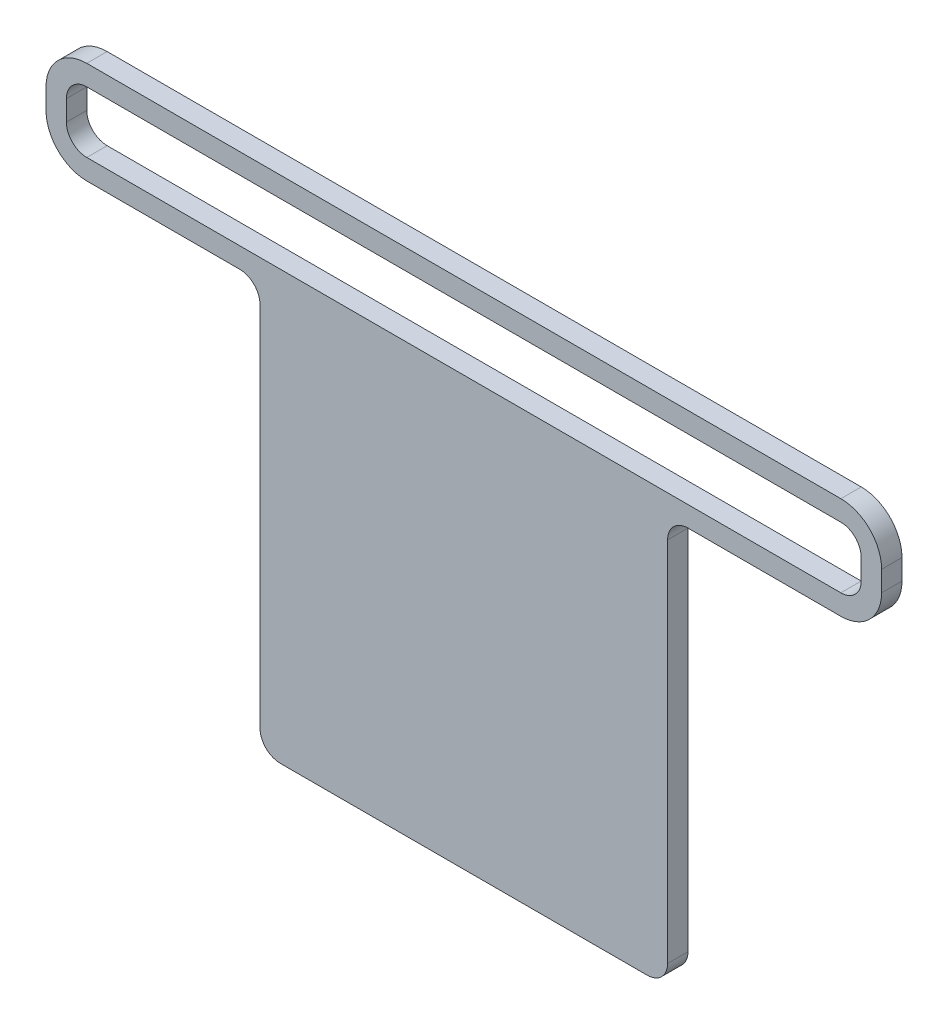
SolidWorks part; units mm, degrees
ref_plane "Front Plane" through (0, 0, 0) normal (0, 0, 1) x (1, 0, 0)
ref_plane "Top Plane" through (0, 0, 0) normal (0, 1, 0) x (1, 0, 0)
ref_plane "Right Plane" through (0, 0, 0) normal (1, 0, 0) x (0, 0, -1)
sketch "Sketch1" plane through (0, 0, 0) normal (0, 0, 1) x (1, 0, 0)
  line L0 (105.7044, 0) -> (143.2044, 0)
  line L2 (0.7044, -5) -> (0.7044, -95)
  line L3 (5.7044, -100) -> (95.7044, -100)
  line L4 (100.7044, -5) -> (100.7044, -95)
  line L5 (-41.7956, 25) -> (143.2044, 25)
  line L6 (-51.7956, 15) -> (-51.7956, 10)
  line L7 (-41.7956, 0) -> (-4.2956, 0)
  line L8 (153.2044, 15) -> (153.2044, 10)
  line L9 (-41.7956, 20) -> (143.2044, 20)
  line L10 (-46.7956, 15) -> (-46.7956, 10)
  line L11 (-41.7956, 5) -> (143.2044, 5)
  line L12 (148.2044, 15) -> (148.2044, 10)
  arc A0 (143.2044, 25) -> (153.2044, 15) centre (143.2044, 15) cw
  arc A1 (143.2044, 0) -> (153.2044, 10) centre (143.2044, 10) ccw
  arc A2 (-41.7956, 25) -> (-51.7956, 15) centre (-41.7956, 15) ccw
  arc A3 (-51.7956, 10) -> (-41.7956, 0) centre (-41.7956, 10) ccw
  arc A4 (0.7044, -95) -> (5.7044, -100) centre (5.7044, -95) ccw
  arc A5 (95.7044, -100) -> (100.7044, -95) centre (95.7044, -95) ccw
  arc A6 (105.7044, 0) -> (100.7044, -5) centre (105.7044, -5) ccw
  arc A7 (-4.2956, 0) -> (0.7044, -5) centre (-4.2956, -5) cw
  arc A8 (-41.7956, 20) -> (-46.7956, 15) centre (-41.7956, 15) ccw
  arc A9 (-46.7956, 10) -> (-41.7956, 5) centre (-41.7956, 10) ccw
  arc A10 (143.2044, 5) -> (148.2044, 10) centre (143.2044, 10) ccw
  arc A11 (143.2044, 20) -> (148.2044, 15) centre (143.2044, 15) cw
  point P8 (50.7044, 25)
  point P9 (50.7044, -100)
  point P20 (-51.7956, 25)
  point P23 (-51.7956, 0)
  point P26 (0.7044, -100)
  point P31 (100.7044, 0)
  point P34 (0.7044, 0)
  point P37 (-46.7956, 20)
  point P40 (-46.7956, 5)
  dimension "D8" = 10
  dimension "D9" = 5
  dimension "D1" = 100
  dimension "D2" = 100
  dimension "D3" = 15
  dimension "D4" = 5
  dimension "D5" = 25
  dimension "D6" = 5
  dimension "D7" = 5
  dimension "D10" = 200
extrude "Boss-Extrude1" add sketch "Sketch1" along normal blind 5
